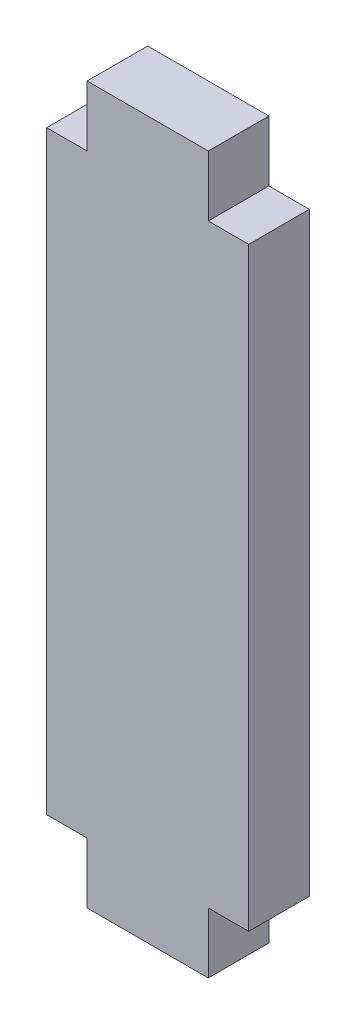
SolidWorks part; units mm, degrees
ref_plane "Front Plane" through (0, 0, 0) normal (0, 0, 1) x (1, 0, 0)
ref_plane "Top Plane" through (0, 0, 0) normal (0, 1, 0) x (1, 0, 0)
ref_plane "Right Plane" through (0, 0, 0) normal (1, 0, 0) x (0, 0, -1)
sketch "Sketch1" plane through (0, 0, 0) normal (0, 0, 1) x (1, 0, 0)
  line L1 (5, -14.725) -> (-5, -14.725)
  line L2 (5, -14.725) -> (5, 14.725)
  line L3 (5, 14.725) -> (-5, 14.725)
  line L4 (-5, -14.725) -> (-5, 14.725)
  line L5 (5, -14.725) -> (-5, 14.725) construction
  line L6 (5, 14.725) -> (-5, -14.725) construction
  line L7 (-3, -14.725) -> (3, -14.725)
  line L8 (-3, -14.725) -> (-3, -17.725)
  line L9 (-3, -17.725) -> (3, -17.725)
  line L10 (3, -14.725) -> (3, -17.725)
  line L11 (-3, 14.725) -> (3, 14.725)
  line L12 (-3, 14.725) -> (-3, 17.725)
  line L13 (-3, 17.725) -> (3, 17.725)
  line L14 (3, 14.725) -> (3, 17.725)
  point P0 (0, 0)
  point P14 (0, -17.725)
  point P15 (0, -14.725)
  point P16 (0, 17.725)
  point P17 (0, 14.725)
  dimension "D1" = 10
  dimension "D2" = 29.45
  dimension "D3" = 6
  dimension "D4" = 3
  dimension "D5" = 3
  dimension "D6" = 6
  dimension "D7" = 0
  dimension "D8" = 0
extrude "Boss-Extrude1" add sketch "Sketch1" along normal blind 3 contours L4 L1 L2 L3 | L3 L14 L13 L12 | L10 L1 L8 L9
